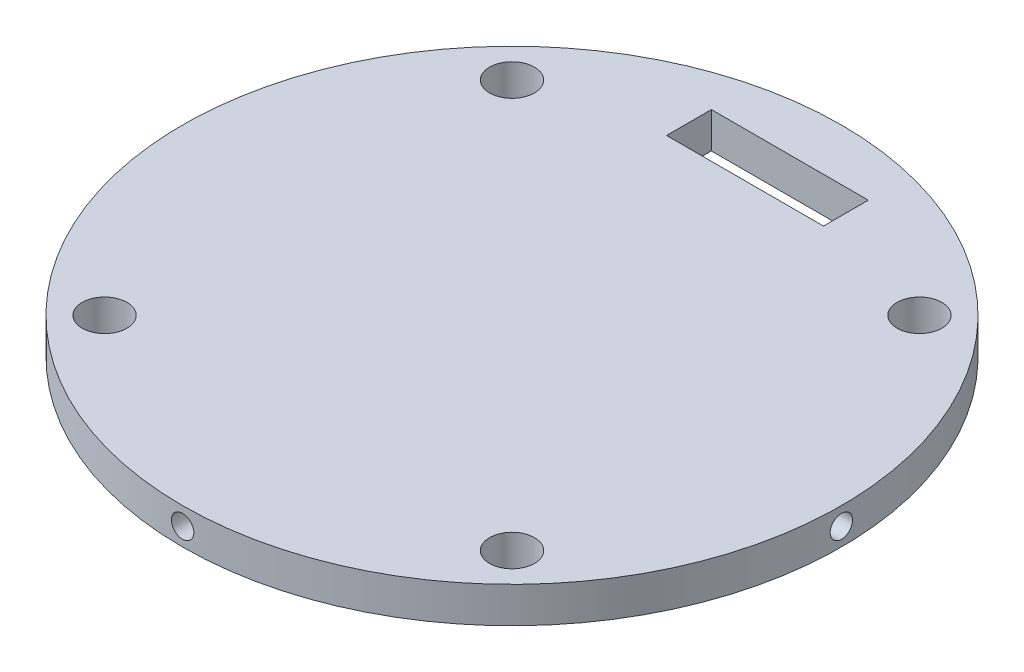
SolidWorks part; units mm, degrees
ref_plane "前视基准面" through (0, 0, 0) normal (0, 0, 1) x (1, 0, 0)
ref_plane "上视基准面" through (0, 0, 0) normal (0, 1, 0) x (1, 0, 0)
ref_plane "右视基准面" through (0, 0, 0) normal (1, 0, 0) x (0, 0, -1)
other "Configuration Table"
sketch "草图1" plane through (0, 0, 0) normal (0, 1, 0) x (1, 0, 0)
  line L0 (0, 0) -> (0, 50000) construction
  line L1 (0, 0) -> (-50000, 0) construction
  line L2 (-17.5, 61.9672) -> (17.5, 61.9672)
  line L4 (-17.5, 61.9672) -> (-17.5, 51.9672)
  line L5 (-17.5, 51.9672) -> (17.5, 51.9672)
  line L6 (17.5, 51.9672) -> (17.5, 61.9672)
  line L8 (0, 0) -> (-35355.3391, 35355.3391) construction
  line L9 (0, 0) -> (35355.3391, 35355.3391) construction
  circle A0 centre (0, 0) radius 73.5
  circle A1 centre (-45.4373, 45.4373) radius 5
  circle A2 centre (-45.4373, -45.4373) radius 5
  circle A3 centre (45.4373, 45.4373) radius 5
  circle A4 centre (45.4373, -45.4373) radius 5
  dimension "D1" = 147
  dimension "D2" = 35
  dimension "D3" = 10
extrude "凸台-拉伸1" add sketch "草图1" along normal blind 8
ref_plane "基准面2" through (0, 0, 73.5) normal (0, 0, 1) x (1, 0, 0)
ref_plane "基准面3" through (0, 0, -73.5) normal (0, 0, 1) x (1, 0, 0)
ref_plane "基准面4" through (73.5, 0, 0) normal (1, 0, 0) x (0, 0, -1)
sketch "草图2" plane through (0, 0, 73.5) normal (0, 0, 1) x (1, 0, 0)
  line L0 (0, 0) -> (0, 8)
  line L1 (-17.5, 8) -> (17.5, 8) construction
  circle A0 centre (0, 4) radius 2.5
extrude "切除-拉伸1" cut sketch "草图2" against normal blind 8 contours L0 A0
mirror "镜向1" about plane through (0, 0, 0) normal (0, 0, 1) of "切除-拉伸1"
sketch "草图3" plane through (73.5, 0, 0) normal (1, 0, 0) x (0, 0, -1)
  line L0 (0, 0) -> (0, 8)
  line L1 (73.5, 8) -> (-73.5, 8) construction
  circle A0 centre (0, 4) radius 2.5
extrude "切除-拉伸3" cut sketch "草图3" against normal blind 8 contours L0 A0 | L0 A0
mirror "镜向2" about plane through (0, 0, 0) normal (1, 0, 0) of "切除-拉伸3"
